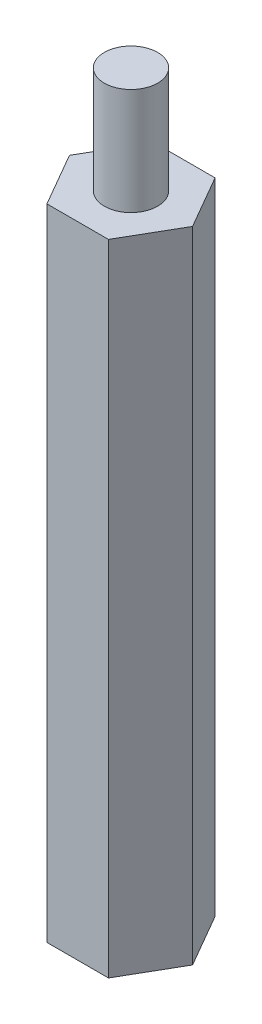
SolidWorks part; units mm, degrees
ref_plane "Front Plane" through (0, 0, 0) normal (0, 0, 1) x (1, 0, 0)
ref_plane "Top Plane" through (0, 0, 0) normal (0, 1, 0) x (1, 0, 0)
ref_plane "Right Plane" through (0, 0, 0) normal (1, 0, 0) x (0, 0, -1)
sketch "Sketch1" plane through (0, 0, 0) normal (0, 1, 0) x (1, 0, 0)
  line L1 (3.6662, -6.35) -> (7.3323, 0)
  line L2 (7.3323, 0) -> (3.6662, 6.35)
  line L3 (3.6662, 6.35) -> (-3.6662, 6.35)
  line L4 (-3.6662, 6.35) -> (-7.3323, 0)
  line L5 (-7.3323, 0) -> (-3.6662, -6.35)
  line L6 (-3.6662, -6.35) -> (3.6662, -6.35)
  circle A0 centre (0, 0) radius 6.35 construction
  dimension "D1" = 12.7
extrude "Boss-Extrude1" add sketch "Sketch1" along normal blind 76.2
sketch "Sketch2" plane through (0, 76.2, 0) normal (0, 1, 0) x (1, 0, 0)
  circle A0 centre (0, 0) radius 3.175
  dimension "D1" = 6.35
extrude "Boss-Extrude2" add sketch "Sketch2" along normal blind 12.7
